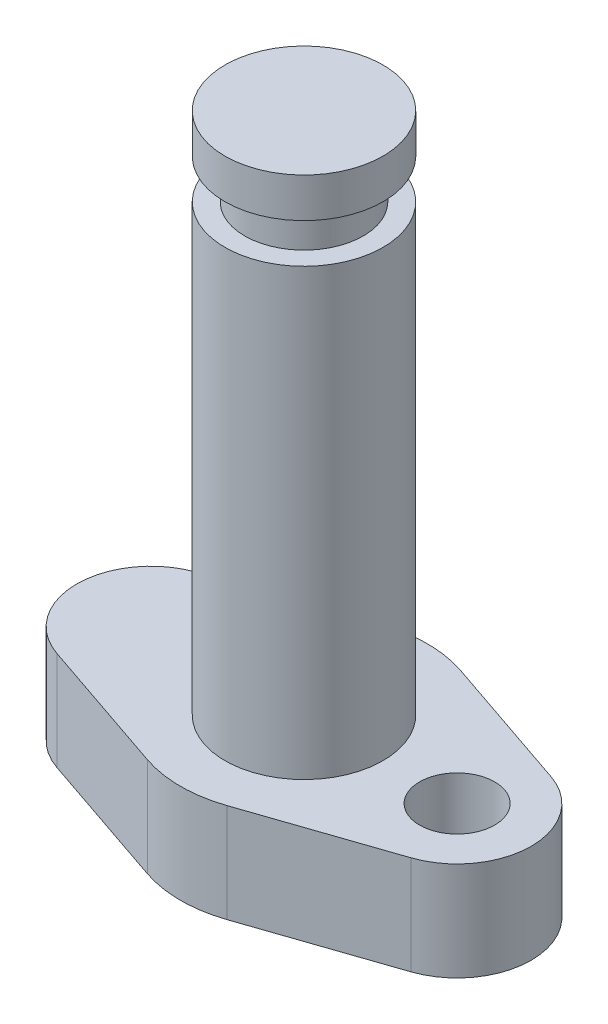
SolidWorks part; units mm, degrees
ref_plane "Front Plane" through (0, 0, 0) normal (0, 0, 1) x (1, 0, 0)
ref_plane "Top Plane" through (0, 0, 0) normal (0, 1, 0) x (1, 0, 0)
ref_plane "Right Plane" through (0, 0, 0) normal (1, 0, 0) x (0, 0, -1)
sketch "Sketch1" plane through (0, 0, 0) normal (0, 1, 0) x (1, 0, 0)
  line L0 (-8.9597, 3.5495) -> (-2.0161, 5.9159)
  line L1 (-8.9597, -3.5495) -> (-2.0161, -5.9159)
  line L2 (2.0161, 5.9159) -> (8.9597, 3.5495)
  line L3 (8.9597, -3.5495) -> (2.0161, -5.9159)
  circle A0 centre (0, 0) radius 4 construction
  circle A1 centre (0, 0) radius 6.25
  circle A2 centre (7.75, 0) radius 2.5 construction
  circle A3 centre (-7.75, 0) radius 2.5 construction
  circle A4 centre (-7.75, 0) radius 3.75
  circle A5 centre (7.75, 0) radius 3.75
  dimension "D1" = 7.5
  dimension "D2" = 8
  dimension "D3" = 12.5
  dimension "D4" = 5
extrude "Boss-Extrude1" add sketch "Sketch1" along normal blind 5 contours A1 A4 A3 | A1 A4 A3 | A5 A1 A4 | A4 L1 A1 | A5 A1 L3 | A1 A5 A2 | A5 A1 A2 | A5 L2 A1 | A4 A1 L0
sketch "Sketch2" plane through (0, 5, 0) normal (0, 1, 0) x (1, 0, 0)
  line L0 (0, -6.25) -> (0, 6.25) construction
  line L1 (11.5, 0) -> (-11.5, 0) construction
  arc A0 (-2.0161, -5.9159) -> (2.0161, -5.9159) centre (0, 0) ccw construction
  arc A1 (2.0161, 5.9159) -> (-2.0161, 5.9159) centre (0, 0) ccw construction
  arc A2 (8.9597, -3.5495) -> (8.9597, 3.5495) centre (7.75, 0) ccw construction
  arc A3 (-8.9597, 3.5495) -> (-8.9597, -3.5495) centre (-7.75, 0) ccw construction
  circle A4 centre (0, 0) radius 4
extrude "Boss-Extrude2" add sketch "Sketch2" along normal blind 22.5
sketch "Sketch3" plane through (0, 27.5, 0) normal (0, 1, 0) x (1, 0, 0)
  circle A0 centre (0, 0) radius 3
  dimension "D1" = 6
extrude "Boss-Extrude3" add sketch "Sketch3" along normal blind 2
sketch "Sketch4" plane through (0, 29.5, 0) normal (0, 1, 0) x (1, 0, 0)
  circle A0 centre (0, 0) radius 4
extrude "Boss-Extrude4" add sketch "Sketch4" along normal blind 2
hole_wizard "#6 Clearance Hole1" positions "Sketch5" profile "Sketch6" hole size "#6" standard "ANSI Inch"
sketch "Sketch5" plane through (0, 5, 0) normal (0, 1, 0) x (1, 0, 0)
  point P3 (7.75, 0)
  point P6 (0, 0)
sketch "Sketch6" plane through (7.75, 5, 0) normal (1, 0, 0) x (0, 0, 1)
  line L0 (0, 0) -> (0, 5)
  line L1 (0, 5) -> (1.8986, 5)
  line L2 (1.8986, 5) -> (1.8986, 0)
  line L5 (1.8986, 0) -> (0, 0)
  line L11 (0, -6.35) -> (0, 107.95) construction
  dimension "Thru Hole Dia." = 3.7973
  dimension "Thru Hole Depth" = 5
